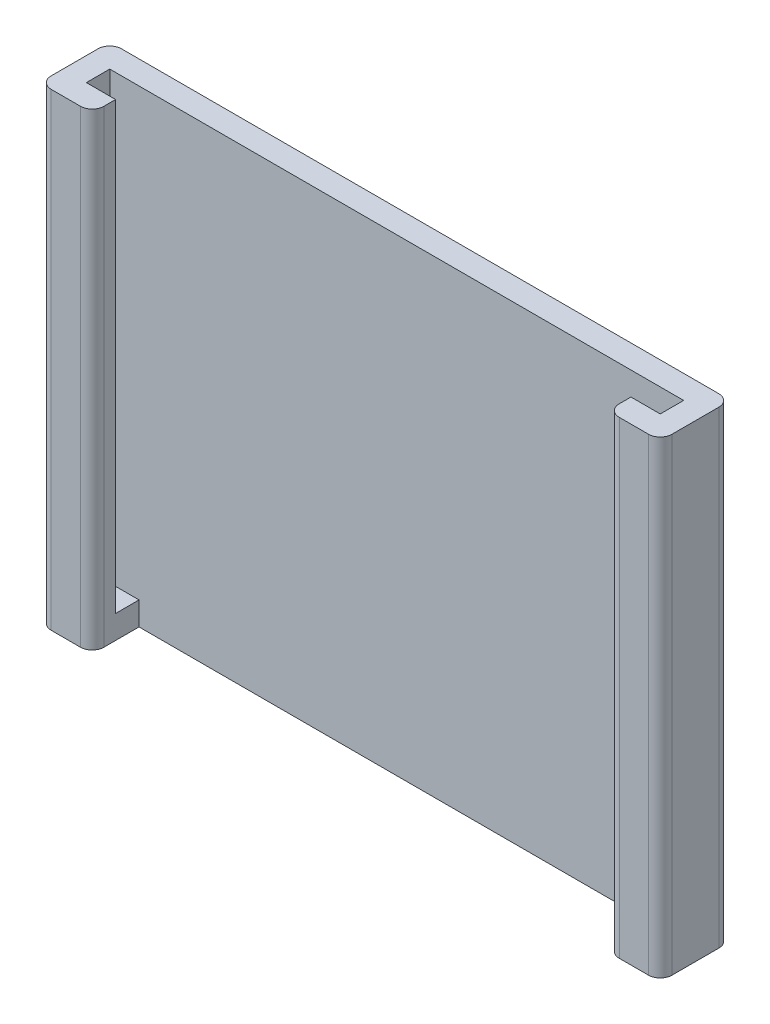
SolidWorks part; units mm, degrees
ref_plane "Front Plane" through (0, 0, 0) normal (0, 0, 1) x (1, 0, 0)
ref_plane "Top Plane" through (0, 0, 0) normal (0, 1, 0) x (1, 0, 0)
ref_plane "Right Plane" through (0, 0, 0) normal (1, 0, 0) x (0, 0, -1)
sketch "Sketch1" plane through (0, 0, 0) normal (0, 1, 0) x (1, 0, 0)
  line L1 (26.5, 2) -> (-26.5, 2)
  line L2 (-26.5, 2) -> (-26.5, -4)
  line L3 (-26.5, -4) -> (-22, -4)
  line L4 (-22, -4) -> (-22, -2)
  line L5 (-22, -2) -> (-24.5, -2)
  line L6 (24.5, 0) -> (-24.5, 0)
  line L7 (-24.5, 0) -> (-24.5, -2)
  line L8 (0, 0) -> (0, -9.0675) construction
  line L9 (26.5, 2) -> (26.5, -4)
  line L10 (26.5, -4) -> (22, -4)
  line L11 (22, -4) -> (22, -2)
  line L12 (22, -2) -> (24.5, -2)
  line L13 (24.5, 0) -> (24.5, -2)
  point P9 (-24.5, -1)
  dimension "D2" = 2
  dimension "D3" = 2.5
  dimension "D4" = 6
  dimension "D6" = 2
extrude "Boss-Extrude1" add sketch "Sketch1" along normal blind 40 contours L7 L5 L4 L3 L2 L1 L9 L10 L11 L12 L13 L6
sketch "Sketch2" plane through (0, 0, 0) normal (0, 1, 0) x (1, 0, 0)
  line L0 (0, 0) -> (0, -17.2218) construction
  line L1 (-24.5, 0) -> (-22, 0)
  line L2 (-24.5, 0) -> (-24.5, -2)
  line L3 (-24.5, -2) -> (-22, -2)
  line L4 (-22, 0) -> (-22, -2)
  line L5 (24.5, -2) -> (22, -2)
  line L6 (22, 0) -> (22, -2)
  line L7 (24.5, 0) -> (22, 0)
  line L8 (24.5, 0) -> (24.5, -2)
extrude "Boss-Extrude2" add sketch "Sketch2" along normal blind 2
fillet "Fillet1" radius 1 6 edges at (22, 20, 4) (-22, 20, 4) (26.5, 20, -2) (26.5, 20, 4) (-26.5, 20, -2) (-26.5, 20, 4)
